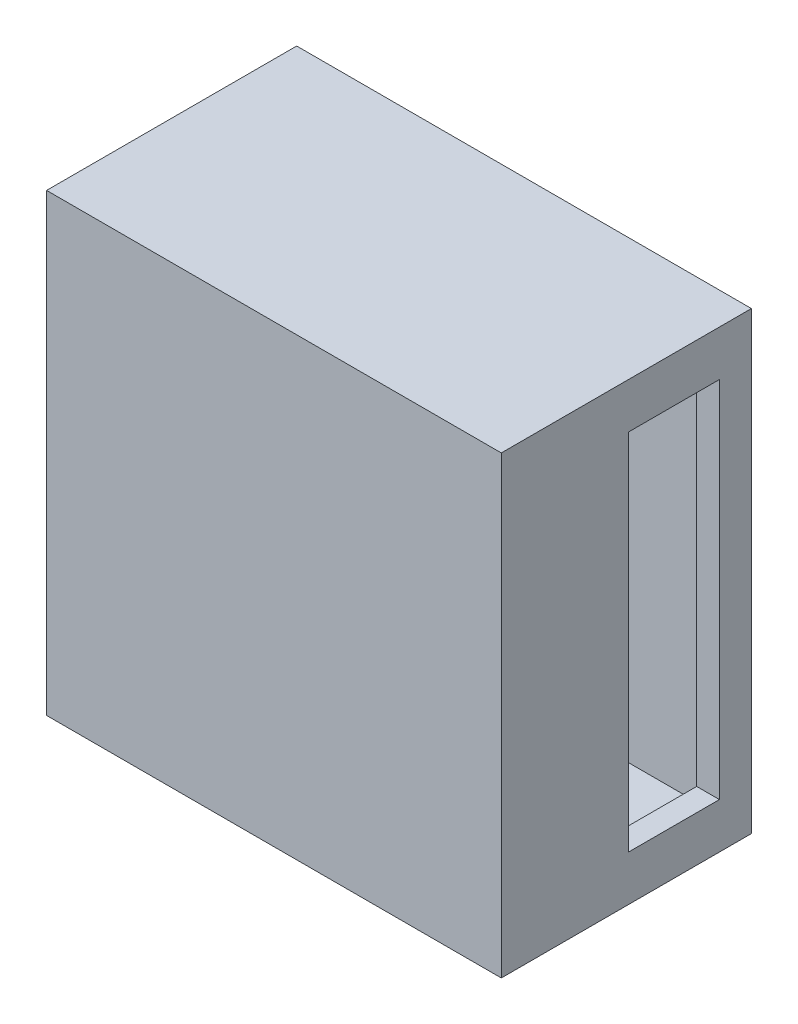
SolidWorks part; units mm, degrees
ref_plane "Front Plane" through (0, 0, 0) normal (0, 0, 1) x (1, 0, 0)
ref_plane "Top Plane" through (0, 0, 0) normal (0, 1, 0) x (1, 0, 0)
ref_plane "Right Plane" through (0, 0, 0) normal (1, 0, 0) x (0, 0, -1)
sketch "Sketch1" plane through (0, 0, 0) normal (0, 0, 1) x (1, 0, 0)
  line L1 (-50, -50) -> (50, -50)
  line L2 (-50, -50) -> (-50, 50)
  line L3 (-50, 50) -> (50, 50)
  line L4 (50, -50) -> (50, 50)
  line L5 (-50, -50) -> (50, 50) construction
  line L6 (-50, 50) -> (50, -50) construction
  point P0 (0, 0)
  dimension "D1" = 100
  dimension "D2" = 100
extrude "Boss-Extrude1" add sketch "Sketch1" along normal blind 50
shell "Shell1" thickness 5
sketch "Sketch2" plane through (50, 0, 0) normal (1, 0, 0) x (0, 0, -1)
  line L0 (-50, -50) -> (0, -50) construction
  line L1 (-27.0369, 40) -> (-7.0369, 40)
  line L2 (-27.0369, 40) -> (-27.0369, -40)
  line L3 (-27.0369, -40) -> (-7.0369, -40)
  line L4 (-7.0369, 40) -> (-7.0369, -40)
  dimension "D1" = 20
  dimension "D2" = 80
  dimension "D3" = 10
extrude "Cut-Extrude1" cut sketch "Sketch2" against normal blind 19
sketch "Sketch3" plane through (0, 0, 50) normal (0, 0, 1) x (1, 0, 0)
  line L1 (-50, 50) -> (50, 50)
  line L2 (-50, 50) -> (-50, -50)
  line L3 (-50, -50) -> (50, -50)
  line L4 (50, 50) -> (50, -50)
extrude "Boss-Extrude2" add sketch "Sketch3" along normal blind 5
